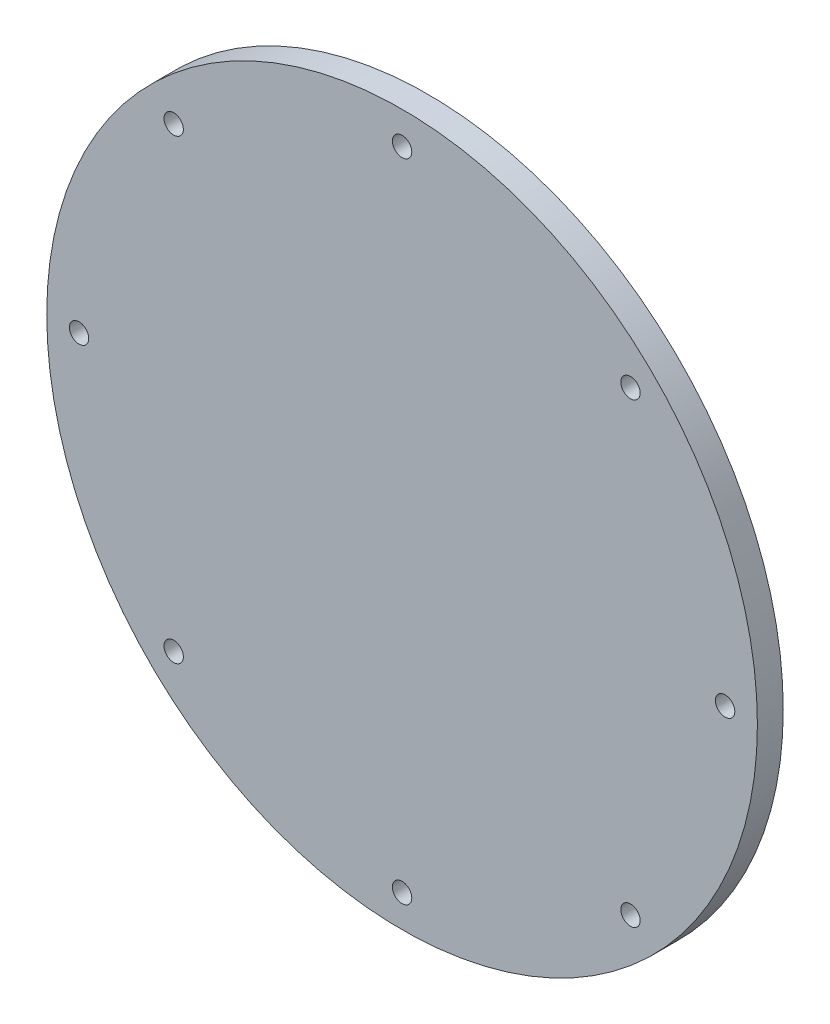
SolidWorks part; units mm, degrees
material "ABS PC"
ref_plane "前视基准面" through (0, 0, 0) normal (0, 0, 1) x (1, 0, 0)
ref_plane "上视基准面" through (0, 0, 0) normal (0, 1, 0) x (1, 0, 0)
ref_plane "右视基准面" through (0, 0, 0) normal (1, 0, 0) x (0, 0, -1)
sketch "草图1" plane through (0, 0, 0) normal (0, 0, 1) x (1, 0, 0)
  circle A0 centre (0, 0) radius 110
  dimension "D1" = 220
extrude "凸台-拉伸1" add sketch "草图1" along normal blind 8
sketch "草图2" plane through (0, 0, 8) normal (0, 0, 1) x (1, 0, 0)
  circle A0 centre (0, 0) radius 100 construction
  circle A1 centre (0, 100) radius 3
  circle A2 centre (70.7107, 70.7107) radius 3
  circle A3 centre (100, 0) radius 3
  circle A4 centre (70.7107, -70.7107) radius 3
  circle A5 centre (0, -100) radius 3
  circle A6 centre (-70.7107, -70.7107) radius 3
  circle A7 centre (-100, 0) radius 3
  circle A8 centre (-70.7107, 70.7107) radius 3
  point P21 (0, 0)
  dimension "D1" = 8
  dimension "D2" = 200
  dimension "D3" = 6
extrude "切除-拉伸1" cut sketch "草图2" against normal blind 8
